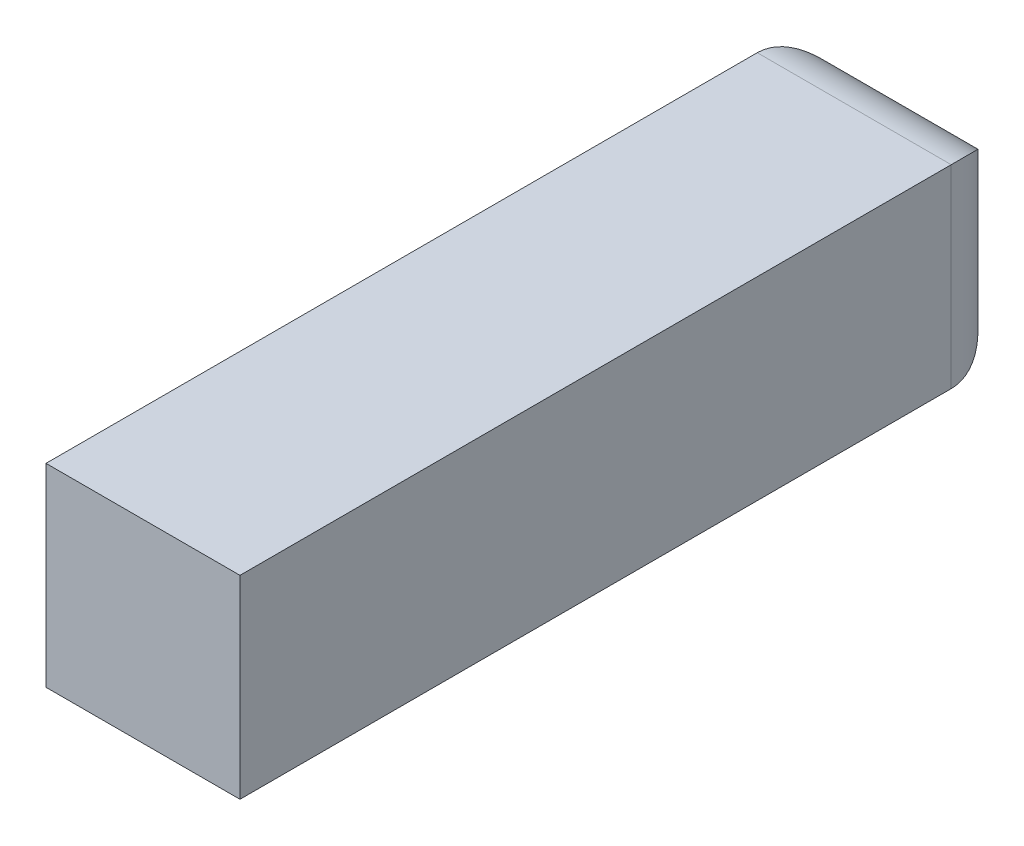
SolidWorks part; units mm, degrees
material "PE haute densité"
ref_plane "Plan de face" through (0, 0, 0) normal (0, 0, 1) x (1, 0, 0)
ref_plane "Plan de dessus" through (0, 0, 0) normal (0, 1, 0) x (1, 0, 0)
ref_plane "Plan de droite" through (0, 0, 0) normal (1, 0, 0) x (0, 0, -1)
sketch "Esquisse1" plane through (0, 0, 0) normal (0, 0, 1) x (1, 0, 0)
  line L0 (0, 39.3066) -> (0, -42.5912) construction
  line L1 (-15, 15) -> (15, 15)
  line L2 (-15, 15) -> (-15, -15)
  line L3 (-15, -15) -> (15, -15)
  line L4 (15, 15) -> (15, -15)
  line L5 (-45.5526, 0) -> (37.6591, 0) construction
  dimension "D1" = 30
  dimension "D2" = 30
extrude "Boss.-Extru.1" add sketch "Esquisse1" along normal blind 120
fillet "Congé2" radius 10 4 edges at (0, -15, 0) (-15, 0, 0) (0, 15, 0) (15, 0, 0)
